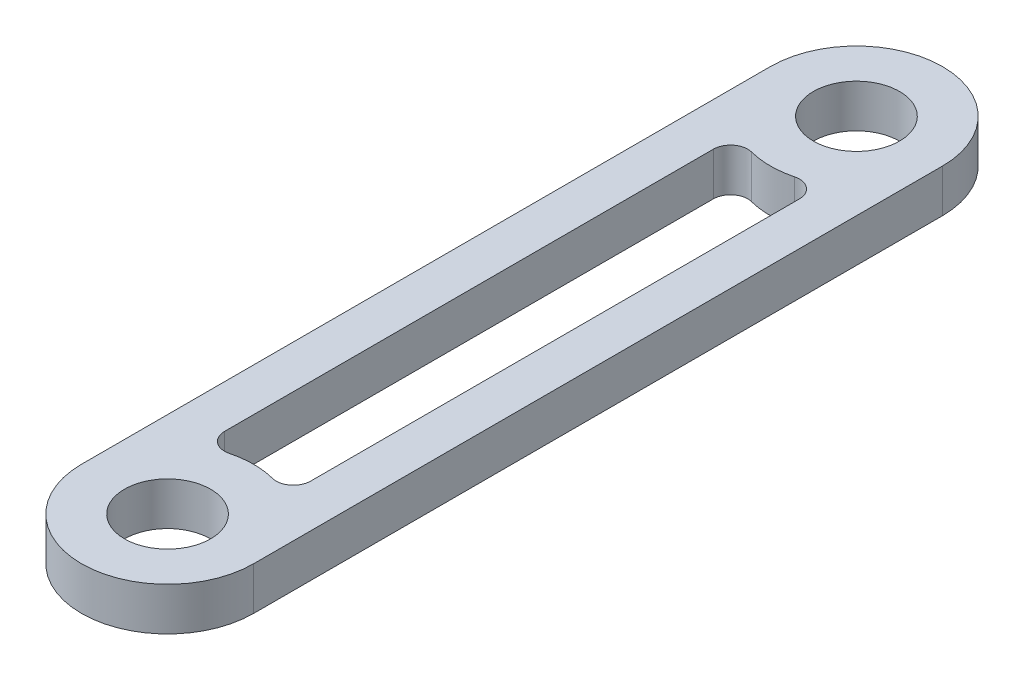
SolidWorks part; units mm, degrees
ref_plane "前视基准面" through (0, 0, 0) normal (0, 0, 1) x (1, 0, 0)
ref_plane "上视基准面" through (0, 0, 0) normal (0, 1, 0) x (1, 0, 0)
ref_plane "右视基准面" through (0, 0, 0) normal (1, 0, 0) x (0, 0, -1)
other "Configuration Table"
sketch "草图1" plane through (0, 0, 0) normal (0, 1, 0) x (1, 0, 0)
  line L0 (0, 0) -> (0, 80) construction
  line L1 (-10, 80) -> (-10, 0)
  line L2 (10, 80) -> (10, 0)
  circle A0 centre (0, 0) radius 5
  circle A1 centre (0, 80) radius 5
  arc A2 (10, 80) -> (-10, 80) centre (0, 80) ccw
  arc A3 (-10, 0) -> (10, 0) centre (0, 0) ccw
  dimension "D1" = 20
  dimension "D2" = 80
  dimension "D3" = 10
extrude "凸台-拉伸1" add sketch "草图1" along normal blind 5
sketch "草图2" plane through (0, 5, 0) normal (0, 1, 0) x (1, 0, 0)
  line L2 (-5, 80) -> (-5, 0)
  line L3 (-5, 80) -> (-5, 0)
  line L5 (5, 80) -> (5, 0)
  line L6 (5, 80) -> (5, 0)
  circle A13 centre (0, 0) radius 10
  circle A14 centre (0, 0) radius 10
  circle A16 centre (0, 80) radius 10
  circle A17 centre (0, 80) radius 10
  dimension "D1" = 5
  dimension "D2" = 5
  dimension "D3" = 5
  dimension "D4" = 5
extrude "切除-拉伸1" cut sketch "草图2" against normal through all contours A17 L3 A14 L6
fillet "圆角1" radius 2 4 edges at (5, 2.5, -71.3397) (5, 2.5, -8.6603) (-5, 2.5, -8.6603) (-5, 2.5, -71.3397)
